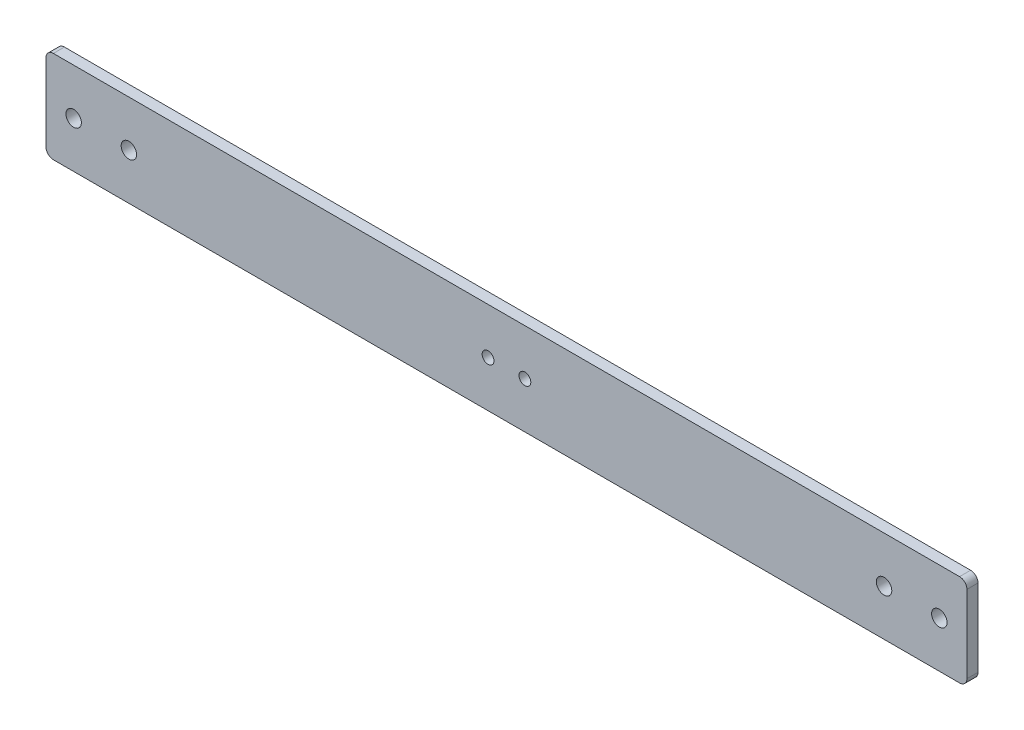
SolidWorks part; units mm, degrees
ref_plane "前视基准面" through (0, 0, 0) normal (0, 0, 1) x (1, 0, 0)
ref_plane "上视基准面" through (0, 0, 0) normal (0, 1, 0) x (1, 0, 0)
ref_plane "右视基准面" through (0, 0, 0) normal (1, 0, 0) x (0, 0, -1)
sketch "草图1" plane through (0, 0, 0) normal (0, 0, 1) x (1, 0, 0)
  line L1 (-125, -12.5) -> (125, -12.5)
  line L2 (-125, -12.5) -> (-125, 12.5)
  line L3 (-125, 12.5) -> (125, 12.5)
  line L4 (125, -12.5) -> (125, 12.5)
  line L5 (-125, -12.5) -> (125, 12.5) construction
  line L6 (-125, 12.5) -> (125, -12.5) construction
  point P0 (0, 0)
  dimension "D1" = 25
  dimension "D2" = 250
extrude "凸台-拉伸1" add sketch "草图1" along normal blind 3
sketch "草图2" plane through (0, 0, 3) normal (0, 0, 1) x (1, 0, 0)
  line L0 (0, 0) -> (50000, 0) construction
  line L1 (-125, 12.5) -> (-125, -12.5) construction
  line L2 (0, 0) -> (0, 50000) construction
  circle A0 centre (-117.5, 0) radius 2.1
  circle A1 centre (-102.5, 0) radius 2.1
  circle A2 centre (102.5, 0) radius 2.1
  circle A3 centre (117.5, 0) radius 2.1
  circle A4 centre (-5, 0) radius 1.6
  circle A5 centre (5, 0) radius 1.6
  dimension "D1" = 4.2
  dimension "D2" = 4.2
  dimension "D5" = 3.2
  dimension "D3" = 15
  dimension "D4" = 7.5
  dimension "D6" = 10
extrude "切除-拉伸1" cut sketch "草图2" against normal blind 3
fillet "圆角1" radius 2 4 edges at (125, -12.5, 1.5) (125, 12.5, 1.5) (-125, -12.5, 1.5) (-125, 12.5, 1.5)
